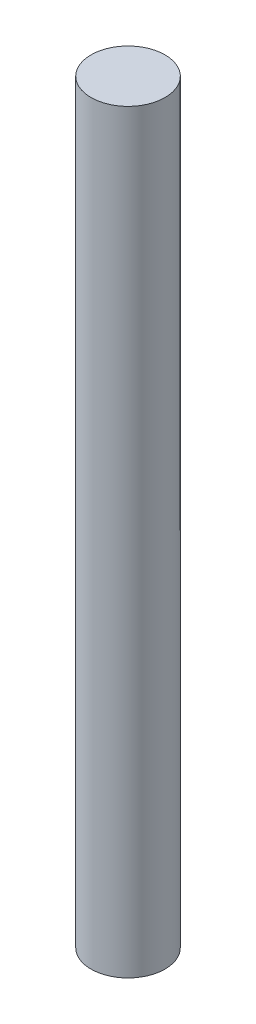
SolidWorks part; units mm, degrees
ref_plane "前视基准面" through (0, 0, 0) normal (0, 0, 1) x (1, 0, 0)
ref_plane "上视基准面" through (0, 0, 0) normal (0, 1, 0) x (1, 0, 0)
ref_plane "右视基准面" through (0, 0, 0) normal (1, 0, 0) x (0, 0, -1)
other "Configuration Table"
sketch "草图1" plane through (0, 0, 0) normal (0, 1, 0) x (1, 0, 0)
  circle A0 centre (0, 0) radius 1.75
  dimension "D1" = 3.5
extrude "凸台-拉伸1" add sketch "草图1" along normal mid plane 35.7
